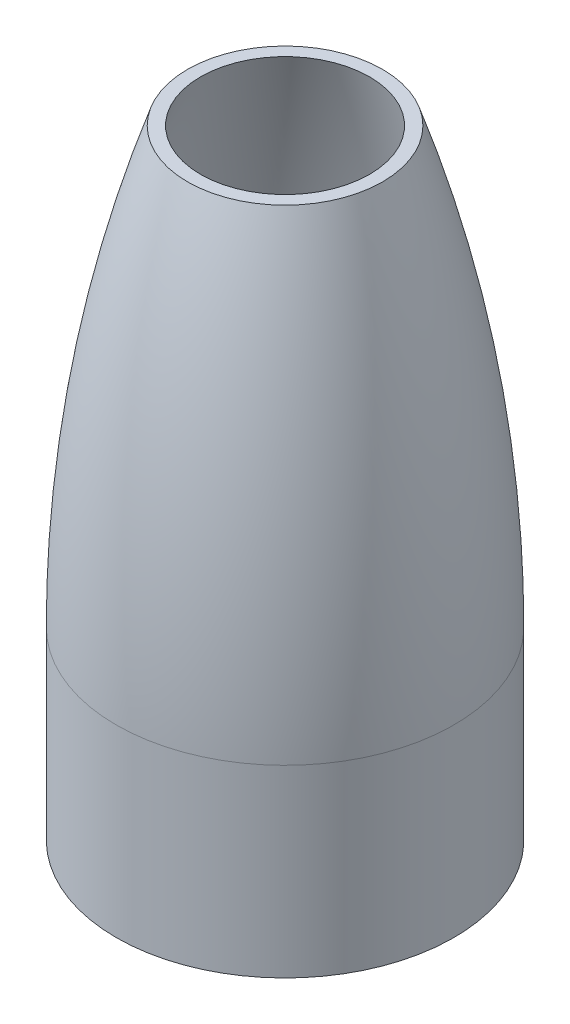
SolidWorks part; units mm, degrees
material "Wrought Stainless Steel"
ref_plane "Front Plane" through (0, 0, 0) normal (0, 0, 1) x (1, 0, 0)
ref_plane "Top Plane" through (0, 0, 0) normal (0, 1, 0) x (1, 0, 0)
ref_plane "Right Plane" through (0, 0, 0) normal (1, 0, 0) x (0, 0, -1)
sketch "Sketch1" plane through (0, 0, 0) normal (0, 0, 1) x (1, 0, 0)
  line L0 (0, 62.0992) -> (0, -38.7008) construction
  line L1 (13.7682, 62.0992) -> (15.88, 62.0992)
  line L2 (27.5, -8.7008) -> (27.5, -38.7008)
  line L3 (27.5, -38.7008) -> (25.5, -38.7008)
  line L4 (25.5, -36.7008) -> (25.5, -38.7008)
  line L5 (25.5, -8.7008) -> (25.5, -36.7008)
  line L7 (27.5, -38.7008) -> (0, -38.7008) construction
  line L8 (0, 62.0992) -> (15.88, 62.0992) construction
  line L9 (0, 60.0992) -> (14.439, 60.0992) construction
  line L10 (25.5, -36.7008) -> (0, -36.7008) construction
  arc A0 (27.5, -8.7008) -> (15.88, 62.0992) centre (-194.0002, -8.7008) ccw
  arc A1 (25.5, -8.7008) -> (14.439, 60.0992) centre (-194.0002, -8.7008) ccw
  arc A2 (25.5, -8.7008) -> (13.7682, 62.0992) centre (-194.0002, -8.7008) ccw
  dimension "D1" = 15.88
  dimension "D4" = 30
  dimension "D5" = 2
  dimension "D2" = 27.5
  dimension "D3" = 100.8
revolve "Revolve1" add sketch "Sketch1" angle 360 about L0
